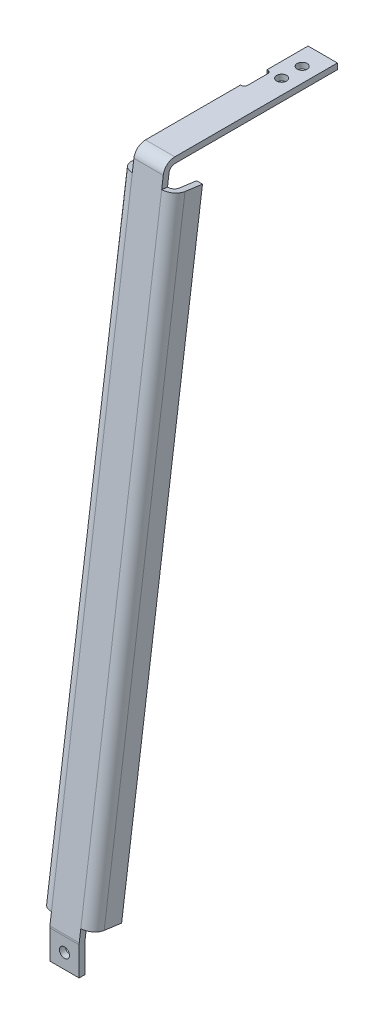
SolidWorks part; units mm, degrees
other "Roof Support Arm 2 Right"
ref_plane "Front Plane" through (0, 0, 0) normal (0, 0, 1) x (1, 0, 0)
ref_plane "Top Plane" through (0, 0, 0) normal (0, 1, 0) x (1, 0, 0)
ref_plane "Right Plane" through (0, 0, 0) normal (1, 0, 0) x (0, 0, -1)
sketch3d "Formed Web Section Sketch datum points"
  point P0 (-30, 0, 0)
  point P1 (-30, 10, 0)
  point P2 (-30, 0, 10)
ref_plane "Formed Web Section Sketch plane" through (-30, 0, 0) normal (1, 0, 0) x (0, 0, -1)
sketch "Formed Web Section Sketch" plane through (-30, 0, 0) normal (1, 0, 0) x (0, 0, -1)
  line L0 (-22, -64) -> (-77.3775, -64)
  line L1 (-81.3416, -67.4653) -> (-109.9641, -279.6667)
  line L2 (-110, -280.2014) -> (-110, -290)
  line L3 (-110, -290) -> (-108, -290)
  line L4 (-108, -290) -> (-108, -280.2014)
  line L5 (-107.9821, -279.9341) -> (-79.3595, -67.7327)
  line L6 (-77.3775, -66) -> (-22, -66)
  line L7 (-22, -66) -> (-22, -64)
  arc A0 (-77.3775, -64) -> (-81.3416, -67.4653) centre (-77.3775, -68) ccw
  arc A1 (-109.9641, -279.6667) -> (-110, -280.2014) centre (-106, -280.2014) ccw
  arc A2 (-107.9821, -279.9341) -> (-108, -280.2014) centre (-106, -280.2014) ccw
  arc A3 (-77.3775, -66) -> (-79.3595, -67.7327) centre (-77.3775, -68) ccw
extrude "Formed Web" add sketch "Formed Web Section Sketch" along normal blind 10 separate body
sketch3d "Edge Lip Sketch datum points"
  point P0 (-25, -71.5631, 80.8853)
  point P1 (-15, -71.5631, 80.8853)
  point P2 (-25, -70.2264, 90.7955)
ref_plane "Edge Lip Sketch plane" through (0, -80.9995, 10.9255) normal (0, -0.991, 0.1337) x (-1, 0, 0)
sketch "Edge Lip Sketch" plane through (0, -80.9995, 10.9255) normal (0, -0.991, 0.1337) x (-1, 0, 0)
  line L0 (34, -67.5933) -> (34, -61.5933)
  line L1 (34, -61.5933) -> (32, -61.5933)
  line L2 (32, -61.5933) -> (32, -67.5933)
  line L3 (30, -69.5933) -> (29.9, -69.5933)
  line L4 (29.9, -69.5933) -> (29.9, -71.5933)
  line L5 (29.9, -71.5933) -> (30, -71.5933)
  line L6 (16, -67.5933) -> (16, -61.5933)
  line L7 (16, -61.5933) -> (18, -61.5933)
  line L8 (18, -61.5933) -> (18, -67.5933)
  line L9 (20, -69.5933) -> (20.1, -69.5933)
  line L10 (20.1, -69.5933) -> (20.1, -71.5933)
  line L11 (20.1, -71.5933) -> (20, -71.5933)
  arc A0 (30, -71.5933) -> (34, -67.5933) centre (30, -67.5933) ccw
  arc A1 (30, -69.5933) -> (32, -67.5933) centre (30, -67.5933) ccw
  arc A2 (16, -67.5933) -> (20, -71.5933) centre (20, -67.5933) ccw
  arc A3 (18, -67.5933) -> (20, -69.5933) centre (20, -67.5933) ccw
extrude "Edge Stiffening Lips" add sketch "Edge Lip Sketch" along normal blind 206.1231
sketch3d "Wall Mount Hole Sketch datum points"
  point P0 (0, -63.8, 0)
  point P1 (10, -63.8, 0)
  point P2 (0, -63.8, 10)
ref_plane "Wall Mount Hole Sketch plane" through (0, -63.8, 0) normal (0, -1, 0) x (-1, 0, 0)
sketch "Wall Mount Hole Sketch" plane through (0, -63.8, 0) normal (0, -1, 0) x (-1, 0, 0)
  circle A0 centre (25, -29) radius 1.7
  circle A1 centre (25, -36) radius 1.7
extrude "Wall Mount Holes" cut sketch "Wall Mount Hole Sketch" along normal blind 2.4
sketch3d "Cover Mount Hole Sketch datum points"
  point P0 (0, 0, 107.8)
  point P1 (10, 0, 107.8)
  point P2 (0, 10, 107.8)
ref_plane "Cover Mount Hole Sketch plane" through (0, 0, 107.8) normal (0, 0, 1) x (1, 0, 0)
sketch "Cover Mount Hole Sketch" plane through (0, 0, 107.8) normal (0, 0, 1) x (1, 0, 0)
  circle A0 centre (-25, -285) radius 1.7
extrude "Cover Mount Hole" cut sketch "Cover Mount Hole Sketch" along normal blind 2.4
sketch3d "Frame Mount Relief Sketch datum points"
  point P0 (0, -63.8, 0)
  point P1 (10, -63.8, 0)
  point P2 (0, -63.8, 10)
ref_plane "Frame Mount Relief Sketch plane" through (0, -63.8, 0) normal (0, -1, 0) x (-1, 0, 0)
sketch "Frame Mount Relief Sketch" plane through (0, -63.8, 0) normal (0, -1, 0) x (-1, 0, 0)
  line L0 (30, -36) -> (29.7, -36)
  line L1 (28.7, -37) -> (28.7, -44)
  line L2 (29.7, -45) -> (30, -45)
  line L3 (31, -44) -> (31, -37)
  arc A0 (31, -37) -> (30, -36) centre (30, -37) ccw
  arc A1 (29.7, -36) -> (28.7, -37) centre (29.7, -37) ccw
  arc A2 (28.7, -44) -> (29.7, -45) centre (29.7, -44) ccw
  arc A3 (30, -45) -> (31, -44) centre (30, -44) ccw
extrude "Frame Mount Relief" cut sketch "Frame Mount Relief Sketch" along normal blind 2.4
